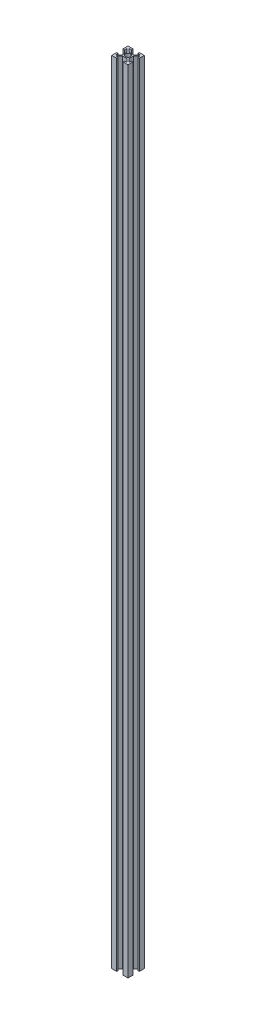
SolidWorks part; units mm, degrees
material "1060 Alloy"
ref_plane "Front Plane" through (0, 0, 0) normal (0, 0, 1) x (1, 0, 0)
ref_plane "Top Plane" through (0, 0, 0) normal (0, 1, 0) x (1, 0, 0)
ref_plane "Right Plane" through (0, 0, 0) normal (1, 0, 0) x (0, 0, -1)
sketch "2020 sketch" plane through (0, 0, 0) normal (0, 1, 0) x (1, 0, 0)
  line L0 (-4, 10) -> (-4, 8)
  line L1 (-10, 10) -> (-4, 10)
  line L2 (-10, 10) -> (-10, 4)
  line L3 (-10, -10) -> (-4, -10)
  line L4 (10, 10) -> (10, 4)
  line L5 (-10, 10) -> (10, -10) construction
  line L6 (-10, -10) -> (10, 10) construction
  line L7 (-4, 8) -> (-7, 8)
  line L8 (-7, 8) -> (-3, 4)
  line L9 (-3, 4) -> (3, 4)
  line L10 (3, 4) -> (7, 8)
  line L11 (7, 8) -> (4, 8)
  line L12 (4, 8) -> (4, 10)
  line L13 (4, 3) -> (4, -3)
  line L14 (8, 7) -> (4, 3)
  line L15 (8, 4) -> (8, 7)
  line L16 (10, 4) -> (8, 4)
  line L17 (8, -4) -> (10, -4)
  line L18 (8, -7) -> (8, -4)
  line L19 (4, -3) -> (8, -7)
  line L20 (3, -4) -> (-3, -4)
  line L21 (7, -8) -> (3, -4)
  line L22 (4, -8) -> (7, -8)
  line L23 (4, -10) -> (4, -8)
  line L24 (-4, -8) -> (-4, -10)
  line L25 (-7, -8) -> (-4, -8)
  line L26 (-3, -4) -> (-7, -8)
  line L27 (-4, -3) -> (-4, 3)
  line L28 (-8, -7) -> (-4, -3)
  line L29 (-8, -4) -> (-8, -7)
  line L30 (-10, -4) -> (-8, -4)
  line L31 (-8, 4) -> (-10, 4)
  line L32 (-8, 7) -> (-8, 4)
  line L33 (-4, 3) -> (-8, 7)
  line L34 (-10, -4) -> (-10, -10)
  line L35 (10, -4) -> (10, -10)
  line L36 (4, 10) -> (10, 10)
  line L37 (4, -10) -> (10, -10)
  circle A0 centre (0, 0) radius 3
  point P0 (0, 0)
  point P14 (4, 9)
  point P42 (0, 0)
  dimension "D9" = 6
  dimension "D1" = 20
  dimension "D2" = 20
  dimension "D3" = 8
  dimension "D4" = 6
  dimension "D5" = 6
  dimension "D6" = 2
  dimension "D7" = 4
  dimension "D8" = 4
extrude "Boss-Extrude1" add sketch "2020 sketch" along normal blind 972.49 contours A0 | L28 L27 L33 L32 L31 L2 L1 L0 L7 L8 L9 L10 L11 L12 L36 L4 L16 L15 L14 L13 L19 L18 L17 L35 L37 L23 L22 L21 L20 L26 L25 L24 L3 L34 L30 L29
